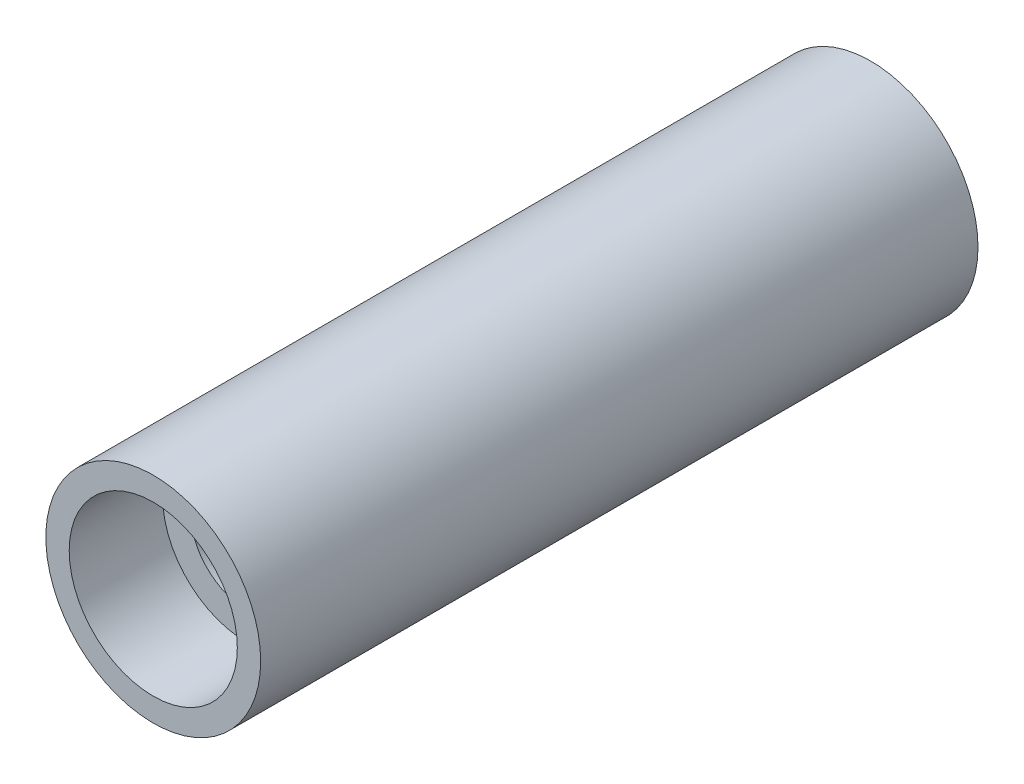
SolidWorks part; units mm, degrees
ref_plane "Front Plane" through (0, 0, 0) normal (0, 0, 1) x (1, 0, 0)
ref_plane "Top Plane" through (0, 0, 0) normal (0, 1, 0) x (1, 0, 0)
ref_plane "Right Plane" through (0, 0, 0) normal (1, 0, 0) x (0, 0, -1)
sketch "Sketch2" plane through (0, 0, 0) normal (0, 0, 1) x (1, 0, 0)
  circle A0 centre (0, 0) radius 5.75
  circle A1 centre (0, 0) radius 3
  dimension "D1" = 6
  dimension "D2" = 11.5
extrude "Boss-Extrude1" add sketch "Sketch2" along normal mid plane 38.4
sketch "Sketch5" plane through (0, 0, 0) normal (1, 0, 0) x (0, 0, -1)
  line L0 (19.2, 0) -> (-19.2, 0) construction
  line L5 (14.2, 0) -> (14.2, 4.5)
  line L6 (14.2, 4.5) -> (19.2, 4.5)
  line L7 (-19.2, 5.75) -> (-19.2, -5.75) construction
  line L10 (19.2, 3) -> (-19.2, 3) construction
  line L11 (19.2, 3) -> (-19.2, 3) construction
  line L12 (19.2, -5.75) -> (19.2, 5.75) construction
  line L13 (19.2, 4.5) -> (19.2, 0)
  line L14 (19.2, 0) -> (14.2, 0)
  line L15 (0, 0) -> (0, 3) construction
  line L16 (-14.2, 0) -> (-14.2, 4.5)
  line L17 (-19.2, 0) -> (-14.2, 0)
  line L18 (-19.2, 4.5) -> (-19.2, 0)
  line L19 (-14.2, 4.5) -> (-19.2, 4.5)
  point P11 (0, 0)
  dimension "D1" = 1.5
  dimension "D2" = 5
revolve "Cut-Revolve1" cut sketch "Sketch5" angle 360 about L0
